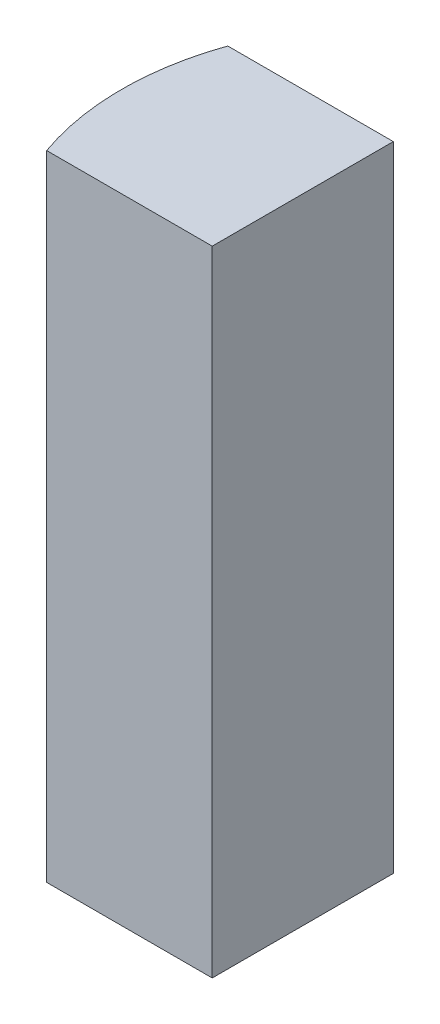
SolidWorks part; units mm, degrees
ref_plane "前视基准面" through (0, 0, 0) normal (0, 0, 1) x (1, 0, 0)
ref_plane "上视基准面" through (0, 0, 0) normal (0, 1, 0) x (1, 0, 0)
ref_plane "右视基准面" through (0, 0, 0) normal (1, 0, 0) x (0, 0, -1)
sketch "草图1" plane through (0, 0, 0) normal (0, 1, 0) x (1, 0, 0)
  line L0 (-56.5685, -20) -> (56.5685, -20)
  line L1 (-56.5685, 20) -> (56.5685, 20)
  line L2 (-20, 56.5685) -> (-20, -56.5685)
  line L3 (20, 56.5685) -> (20, -56.5685)
  circle A0 centre (0, 0) radius 60
  dimension "D1" = 120
  dimension "D2" = 20
  dimension "D3" = 20
  dimension "D4" = 20
  dimension "D5" = 20
extrude "凸台-拉伸1" add sketch "草图1" along normal blind 140 contours L1 A0 L0 L2
